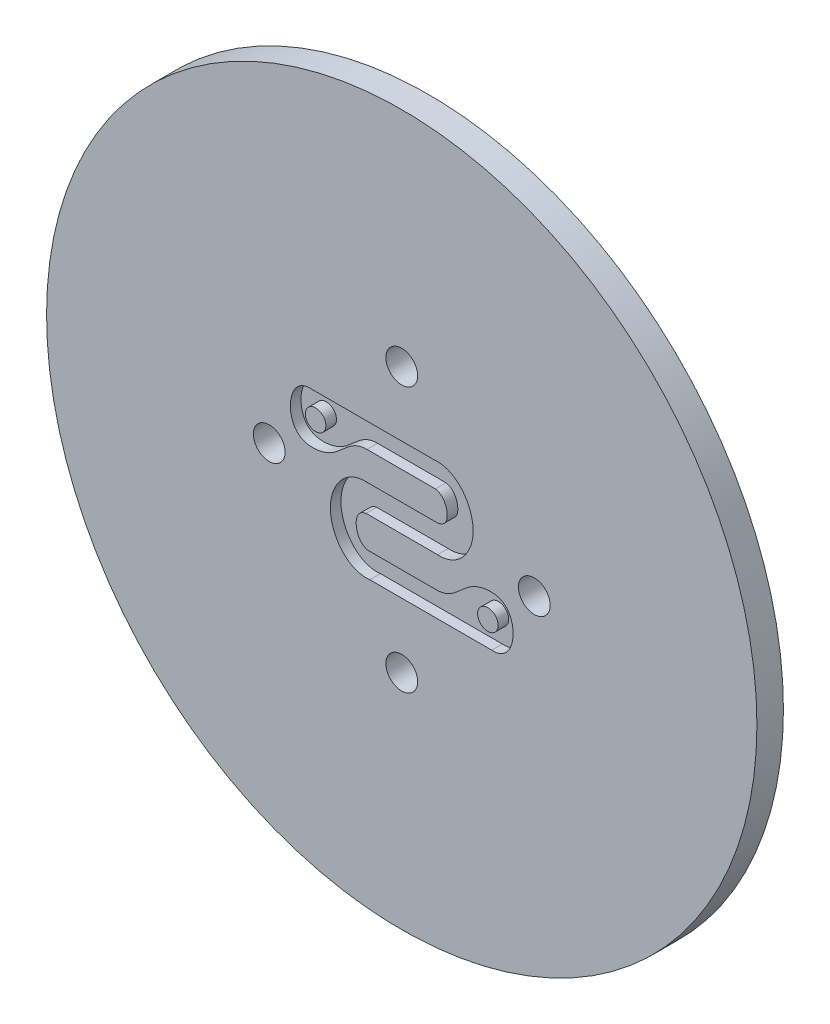
SolidWorks part; units mm, degrees
ref_plane "Płaszczyzna przednia" through (0, 0, 0) normal (0, 0, 1) x (1, 0, 0)
ref_plane "Płaszczyzna górna" through (0, 0, 0) normal (0, 1, 0) x (1, 0, 0)
ref_plane "Płaszczyzna prawa" through (0, 0, 0) normal (1, 0, 0) x (0, 0, -1)
sketch "Szkic1" plane through (0, 0, 0) normal (0, 0, 1) x (1, 0, 0)
  line L0 (0, 0) -> (0, 67) construction
  circle A0 centre (0, 0) radius 67
  circle A1 centre (0, 0) radius 25 construction
  circle A2 centre (0, 25) radius 3
  circle A3 centre (25, 0) radius 3
  circle A4 centre (0, -25) radius 3
  circle A5 centre (-25, 0) radius 3
  point P16 (0, 0)
  dimension "D1" = 134
  dimension "D2" = 6
  dimension "D3" = 50
extrude "Dodanie-wyciągnięcie1" add sketch "Szkic1" along normal blind 5
sketch "Szkic2" plane through (0, 0, 5) normal (0, 0, 1) x (1, 0, 0)
  line L0 (-111.2275, 42.2933) -> (-67.2275, 42.2933) construction
  line L1 (6.0156, 12.8251) -> (-16.9878, 12.8251)
  line L2 (-6.5902, 8.1949) -> (6.3471, 8.1949)
  line L3 (-25, 0) -> (25, 0) construction
  line L4 (0, 25) -> (0, -25) construction
  line L5 (-6.742, 2.8333) -> (6.751, 2.8333)
  line L6 (-6.742, -2.3415) -> (6.751, -2.3415)
  line L7 (-6.0156, -12.8251) -> (16.9878, -12.8251)
  line L8 (6.5902, -8.1949) -> (-6.3471, -8.1949)
  circle A0 centre (-16.2453, 8.1949) radius 1.9374
  circle A2 centre (16.2453, -8.1949) radius 1.9374
  spline S0 degree 3 poles (6.0156, 12.8251) (10.5109, 13.3599) (16.4953, 4.6727) (10.4162, -2.613) (6.751, -2.3415) knots 0 0 0 0 0.552477 1 1 1 1
  spline S1 degree 3 poles (6.751, 2.8333) (8.3665, 3.075) (9.0704, 5.5978) (7.625, 7.9998) (6.3471, 8.1949) knots 0 0 0 0 0.494793 1 1 1 1
  spline S2 degree 3 poles (-16.9878, 12.8251) (-21.3984, 13.1574) (-22.5461, 2.5584) (-11.8282, 3.5339) (-9.7967, 8.1861) (-6.5902, 8.1949) knots 0 0 0 0 0.432021 0.673133 1 1 1 1
  spline S6 degree 3 poles (-6.0156, -12.8251) (-10.5458, -13.3417) (-16.4148, -4.6317) (-10.492, 2.9663) (-6.742, 2.8333) knots 0 0 0 0 0.544343 1 1 1 1
  spline S7 degree 3 poles (-6.742, -2.3415) (-8.3839, -2.6395) (-9.1066, -5.4858) (-7.6357, -7.9911) (-6.3471, -8.1949) knots 0 0 0 0 0.52646 1 1 1 1
  spline S8 degree 3 poles (16.9878, -12.8251) (21.3984, -13.1574) (22.5461, -2.5584) (11.8282, -3.5339) (9.7967, -8.1861) (6.5902, -8.1949) knots 0 0 0 0 0.432021 0.673133 1 1 1 1
  point P22 (0, 0)
  point P30 (0, 0)
  point P31 (10.4317, -1.3048)
  point P32 (8.4686, 4.1887)
extrude "Wytnij-wyciągnięcie1" cut sketch "Szkic2" against normal blind 2
